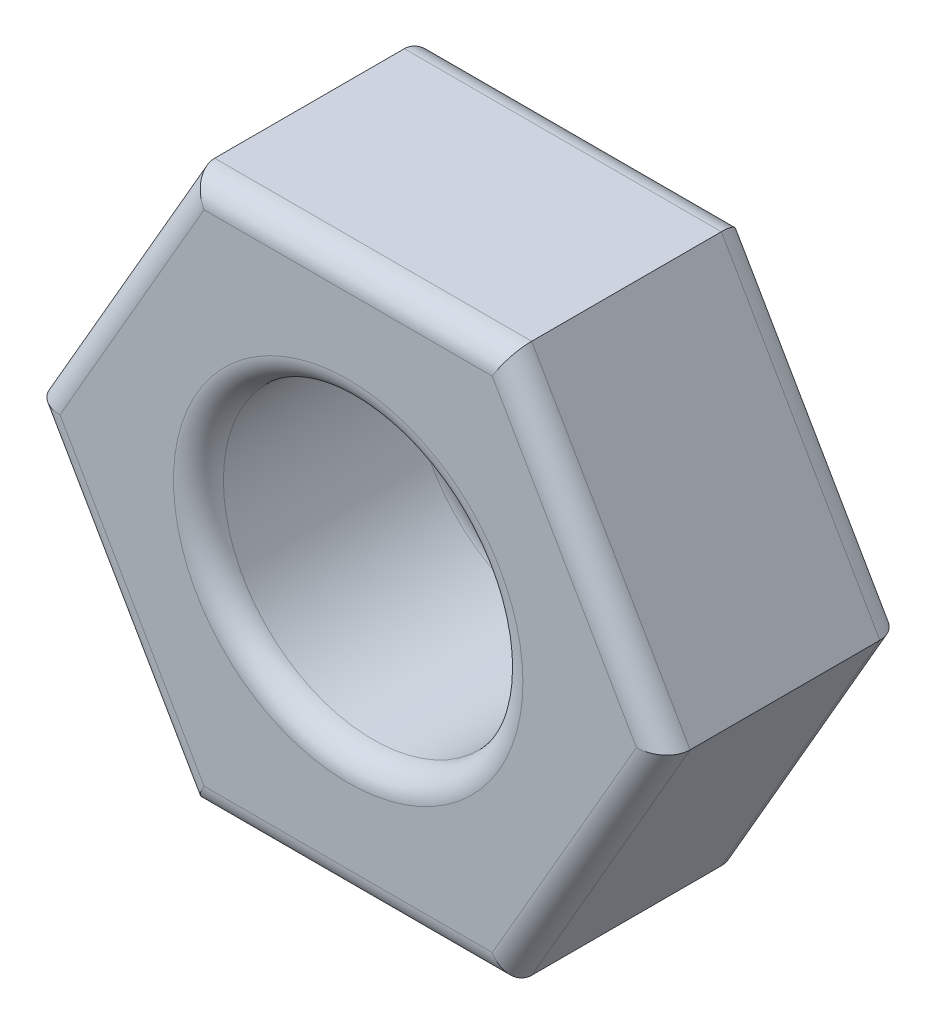
SolidWorks part; units mm, degrees
ref_plane "Спереди" through (0, 0, 0) normal (0, 0, 1) x (1, 0, 0)
ref_plane "Сверху" through (0, 0, 0) normal (0, 1, 0) x (1, 0, 0)
ref_plane "Справа" through (0, 0, 0) normal (1, 0, 0) x (0, 0, -1)
sketch "Эскиз1" plane through (0, 0, 0) normal (0, 0, 1) x (1, 0, 0)
  line L1 (1.5877, 2.75) -> (-1.5877, 2.75)
  line L2 (-1.5877, 2.75) -> (-3.1754, 0)
  line L3 (-3.1754, 0) -> (-1.5877, -2.75)
  line L4 (-1.5877, -2.75) -> (1.5877, -2.75)
  line L5 (1.5877, -2.75) -> (3.1754, 0)
  line L6 (3.1754, 0) -> (1.5877, 2.75)
  circle A0 centre (0, 0) radius 2.75 construction
  circle A1 centre (0, 0) radius 1.5
  dimension "D2" = 3
  dimension "D1" = 5.5
extrude "Бобышка-Вытянуть1" add sketch "Эскиз1" along normal blind 2.4
fillet "Скругление1" radius 0.25 14 edges at (1.5, 0, 0) (0, 2.75, 0) (-2.3816, 1.375, 0) (-2.3816, -1.375, 0) (0, -2.75, 0) (2.3816, -1.375, 0) (2.3816, 1.375, 0) (1.5, 0, 2.4) (2.3816, -1.375, 2.4) (0, -2.75, 2.4) (-2.3816, -1.375, 2.4) (-2.3816, 1.375, 2.4) (0, 2.75, 2.4) (2.3816, 1.375, 2.4)
